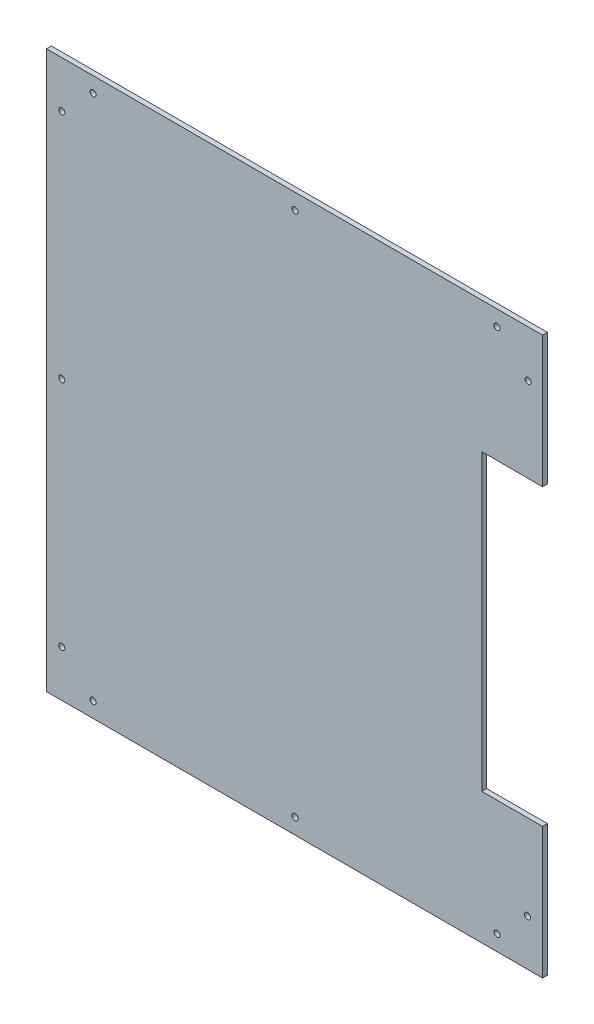
SolidWorks part; units mm, degrees
material "Acrylic (Medium-high impact)"
ref_plane "Front Plane" through (0, 0, 0) normal (0, 0, 1) x (1, 0, 0)
ref_plane "Top Plane" through (0, 0, 0) normal (0, 1, 0) x (1, 0, 0)
ref_plane "Right Plane" through (0, 0, 0) normal (1, 0, 0) x (0, 0, -1)
sketch "Sketch1" plane through (0, 0, 0) normal (0, 0, 1) x (1, 0, 0)
  line L1 (181.3215, 204.546) -> (-226.6785, 204.546)
  line L2 (181.3215, 204.546) -> (181.3215, 96.546)
  line L3 (181.3215, -253.454) -> (-226.6785, -253.454)
  line L4 (-226.6785, 204.546) -> (-226.6785, -253.454)
  line L5 (181.3215, 204.546) -> (-226.6785, -253.454) construction
  line L6 (181.3215, -253.454) -> (-226.6785, 204.546) construction
  line L7 (131.3215, -145.454) -> (131.3215, 96.546)
  line L9 (181.3215, -145.454) -> (181.3215, -253.454)
  line L10 (131.3215, -145.454) -> (181.3215, -145.454)
  line L11 (131.3215, 96.546) -> (181.3215, 96.546)
  circle A0 centre (-214.1785, -215.2469) radius 2.5
  circle A1 centre (-188.4714, -240.9077) radius 2.5
  circle A2 centre (-22.3249, -240.6004) radius 2.5
  circle A3 centre (143.8218, -240.6408) radius 2.5
  circle A4 centre (168.8746, -215.5546) radius 2.5
  circle A5 centre (169.4876, 166.0307) radius 2.5
  circle A6 centre (143.8218, 191.7329) radius 2.5
  circle A7 centre (-22.3249, 191.6925) radius 2.5
  circle A8 centre (-188.4714, 191.9998) radius 2.5
  circle A9 centre (-214.1785, 166.3389) radius 2.5
  circle A10 centre (-214.1785, -24.454) radius 2.5
  point P0 (-22.6785, -24.454)
extrude "Boss-Extrude1" add sketch "Sketch1" along normal blind 4
